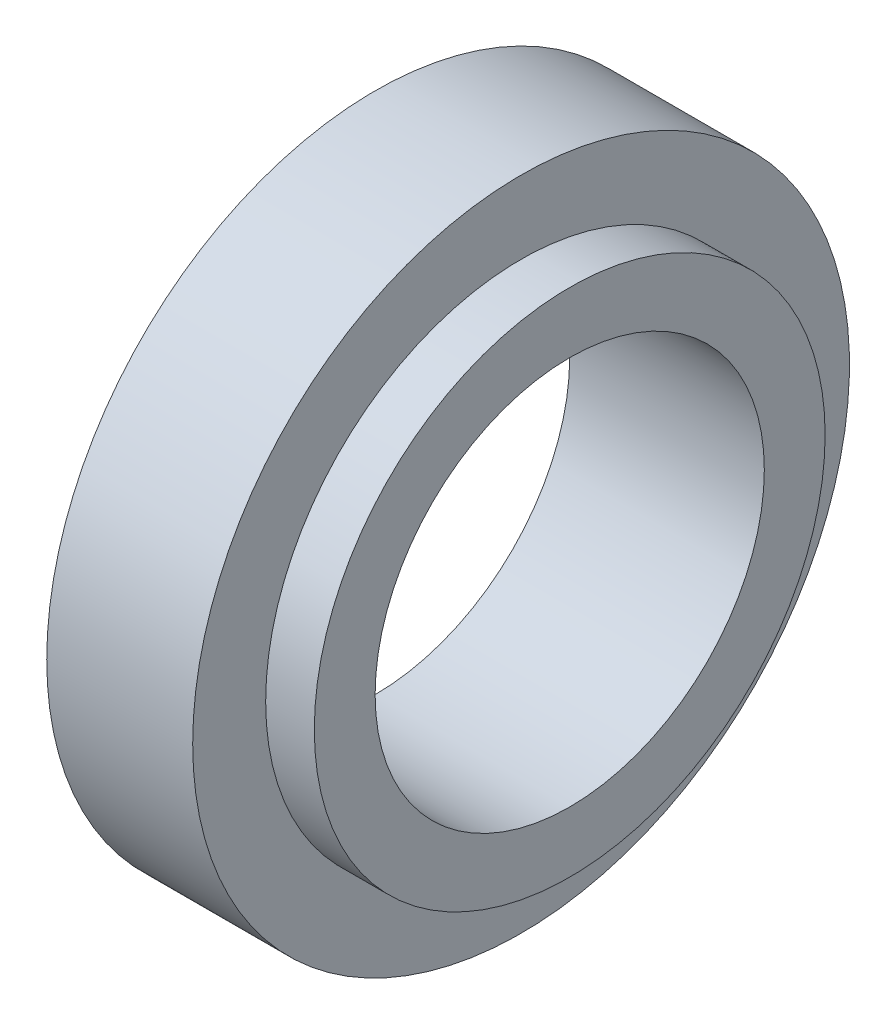
SolidWorks part; units mm, degrees
ref_plane "前视基准面" through (0, 0, 0) normal (0, 0, 1) x (1, 0, 0)
ref_plane "上视基准面" through (0, 0, 0) normal (0, 1, 0) x (1, 0, 0)
ref_plane "右视基准面" through (0, 0, 0) normal (1, 0, 0) x (0, 0, -1)
sketch "草图1" plane through (0, 0, 0) normal (0, 0, 1) x (1, 0, 0)
  line L0 (-5.1064, 0) -> (7.0213, 0) construction
  line L1 (0, 8) -> (0, 13.5)
  line L2 (0, 13.5) -> (6, 13.5)
  line L3 (6, 13.5) -> (6, 10.5)
  line L4 (6, 10.5) -> (8, 10.5)
  line L5 (8, 10.5) -> (8, 8)
  line L6 (0, 8) -> (8, 8)
  dimension "D1" = 2
  dimension "D2" = 6
  dimension "D5" = 8
revolve "旋转1" add sketch "草图1" angle 360 about L0
